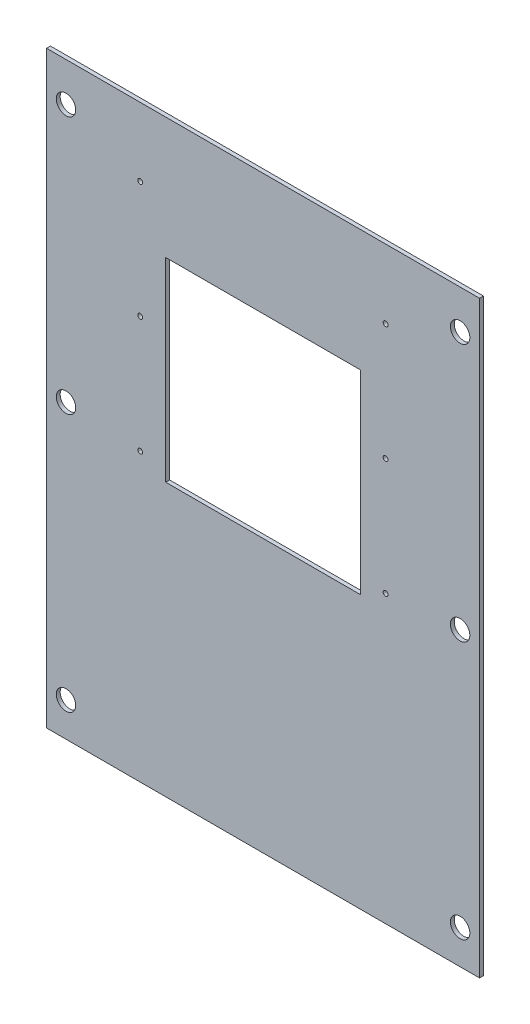
SolidWorks part; units mm, degrees
ref_plane "Front Plane" through (0, 0, 0) normal (0, 0, 1) x (1, 0, 0)
ref_plane "Top Plane" through (0, 0, 0) normal (0, 1, 0) x (1, 0, 0)
ref_plane "Right Plane" through (0, 0, 0) normal (1, 0, 0) x (0, 0, -1)
sketch "Sketch1" plane through (0, 0, 0) normal (0, 0, 1) x (1, 0, 0)
  line L0 (-141.2875, 166.6875) -> (-128.5875, 166.6875) construction
  line L1 (-141.2875, 192.0875) -> (141.2875, 192.0875)
  line L2 (-141.2875, 192.0875) -> (-141.2875, -192.0875)
  line L3 (-141.2875, -192.0875) -> (141.2875, -192.0875)
  line L4 (141.2875, 192.0875) -> (141.2875, -192.0875)
  line L5 (-141.2875, 192.0875) -> (141.2875, -192.0875) construction
  line L6 (-141.2875, -192.0875) -> (141.2875, 192.0875) construction
  line L7 (-128.5875, 166.6875) -> (-128.5875, 192.0875) construction
  line L18 (-128.5875, -1.5875) -> (-128.5875, -169.8625) construction
  line L19 (-63.5064, 112.7125) -> (63.4936, 112.7125)
  line L20 (-63.5064, 112.7125) -> (-63.5064, -14.2875)
  line L21 (-63.5064, -14.2875) -> (63.4936, -14.2875)
  line L22 (63.4936, 112.7125) -> (63.4936, -14.2875)
  line L23 (-63.5064, 112.7125) -> (63.4936, -14.2875) construction
  line L24 (-63.5064, -14.2875) -> (63.4936, 112.7125) construction
  line L25 (-128.5875, 166.6875) -> (-128.5875, -1.5875) construction
  circle A0 centre (-128.5875, 166.6875) radius 6.35
  circle A1 centre (-128.5875, -1.5875) radius 6.35
  circle A2 centre (-128.5875, -169.8625) radius 6.35
  circle A3 centre (128.5875, -1.5875) radius 6.35
  circle A4 centre (128.5875, 166.6875) radius 6.35
  circle A5 centre (128.5875, -169.8625) radius 6.35
  circle A6 centre (-80.1752, 147.3764) radius 1.5875
  circle A7 centre (-80.1752, 71.1764) radius 1.5875
  circle A8 centre (-80.1752, -5.0236) radius 1.5875
  circle A9 centre (79.9707, -5.3952) radius 1.5875
  circle A10 centre (79.9707, 70.8048) radius 1.5875
  circle A11 centre (79.9707, 147.0048) radius 1.5875
  point P0 (0, 0)
  point P20 (-0.0064, 49.2125)
extrude "Boss-Extrude1" add sketch "Sketch1" along normal blind 2.54
